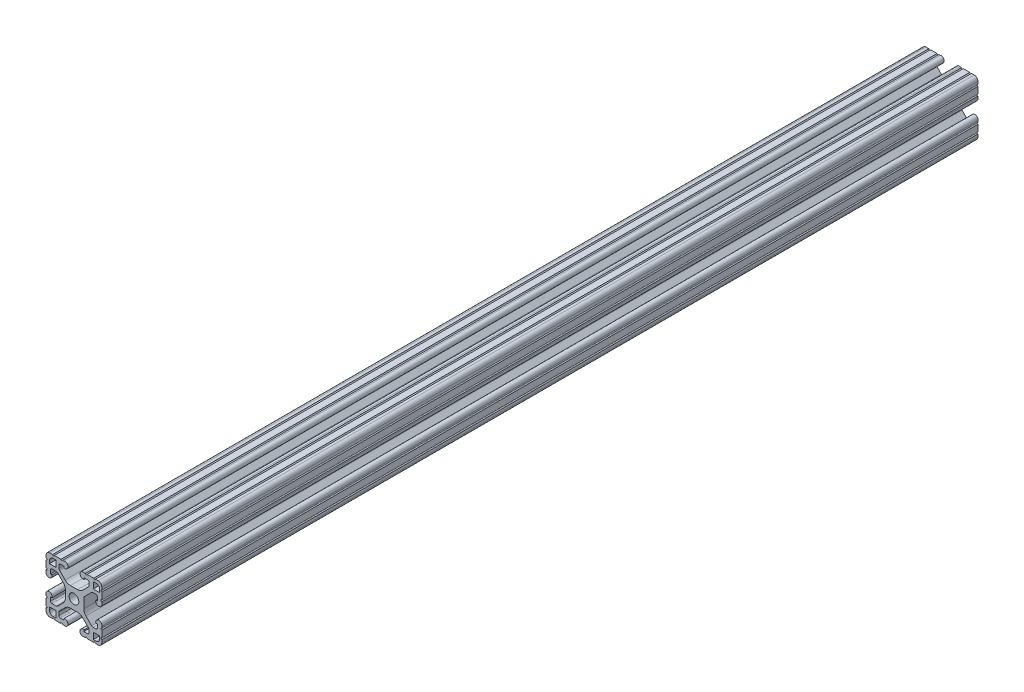
SolidWorks part; units mm, degrees
ref_plane "Front Plane" through (0, 0, 0) normal (0, 0, 1) x (1, 0, 0)
ref_plane "Top Plane" through (0, 0, 0) normal (0, 1, 0) x (1, 0, 0)
ref_plane "Right Plane" through (0, 0, 0) normal (1, 0, 0) x (0, 0, -1)
sketch "Sketch1" plane through (0, 0, 0) normal (0, 0, 1) x (1, 0, 0)
  line L56 (-13.2628, 12.0484) -> (-9.4662, 8.222)
  line L57 (-10.7901, 6.0082) -> (-14.6296, 9.8477)
  line L64 (6.4367, 12.0477) -> (2.5972, 8.2082)
  line L65 (3.2754, 4.5437) -> (8.5794, 9.8477)
  line L70 (-13.3201, -12.0484) -> (-9.5235, -8.222)
  line L71 (-14.6296, -9.8477) -> (-10.7901, -6.0082)
  line L76 (4.7399, -6.0082) -> (8.5794, -9.8477)
  line L77 (2.5399, -8.2082) -> (6.3794, -12.0477)
  line L102 (-5.9169, 6.7437) -> (-0.9384, 6.7437)
  line L103 (3.2754, 4.5437) -> (3.2754, -2.4726)
  line L104 (-0.9957, -6.7437) -> (-5.9742, -6.7437)
  line L105 (-9.3256, -2.4726) -> (-9.3256, 2.4726)
  line L141 (-7.5693, -19.05) -> (-7.5693, -14.986)
  line L153 (-18.4543, 6.801) -> (-19.4703, 6.801)
  line L156 (-19.4703, 6.801) -> (-19.4703, 9.287)
  line L158 (-10.212, 14.986) -> (-10.212, 15.986)
  line L159 (-10.212, 15.986) -> (-12.698, 15.986)
  line L163 (5.876, 15.986) -> (3.39, 15.986)
  line L164 (3.39, 14.986) -> (3.39, 15.986)
  line L167 (11.5177, 6.801) -> (12.5177, 6.801)
  line L168 (12.5177, 9.287) -> (12.5177, 6.801)
  line L171 (11.5177, -6.801) -> (12.5177, -6.801)
  line L172 (12.5177, -9.287) -> (12.5177, -6.801)
  line L174 (3.3327, -14.986) -> (3.3327, -15.986)
  line L175 (3.3327, -15.986) -> (5.8187, -15.986)
  line L179 (-12.7553, -15.986) -> (-10.2693, -15.986)
  line L180 (-10.2693, -14.986) -> (-10.2693, -15.986)
  line L181 (-18.4543, -6.801) -> (-19.4543, -6.801)
  line L184 (-19.4543, -6.801) -> (-19.4543, -9.287)
  line L185 (-18.4543, -10.287) -> (-15.6902, -10.287)
  line L186 (-13.7553, -14.986) -> (-13.7553, -13.1049)
  line L187 (6.8187, -14.986) -> (6.8187, -13.1083)
  line L188 (9.64, -10.287) -> (11.5177, -10.287)
  line L189 (9.64, 10.287) -> (11.5177, 10.287)
  line L190 (6.876, 13.1083) -> (6.876, 14.986)
  line L191 (-15.6902, 10.287) -> (-18.4703, 10.287)
  line L192 (-13.698, 13.1049) -> (-13.698, 14.986)
  line L193 (14.1589, 12.5213) -> (14.1589, 14.4213)
  line L198 (14.1589, 12.5213) -> (9.7589, 12.5213)
  line L199 (9.7589, 12.5213) -> (9.7589, 16.9213)
  line L200 (-15.8411, 12.5213) -> (-20.2411, 12.5213)
  line L201 (-15.8411, 12.5213) -> (-15.8411, 16.9213)
  line L202 (-15.8411, 16.9213) -> (-17.7411, 16.9213)
  line L203 (-20.2411, 12.5213) -> (-20.2411, 14.4213)
  line L204 (11.6589, 16.9213) -> (9.7589, 16.9213)
  line L205 (-15.8411, -17.4787) -> (-15.8411, -13.0787)
  line L206 (-15.8411, -17.4787) -> (-17.7411, -17.4787)
  line L207 (-20.2411, -14.9787) -> (-20.2411, -13.0787)
  line L208 (-15.8411, -13.0787) -> (-20.2411, -13.0787)
  line L209 (14.1589, -14.9787) -> (14.1589, -13.0787)
  line L210 (14.1589, -13.0787) -> (9.7589, -13.0787)
  line L211 (9.7589, -17.4787) -> (9.7589, -13.0787)
  line L212 (11.6589, -17.4787) -> (9.7589, -17.4787)
  line L213 (-20.0183, 19.05) -> (-18.0581, 19.05)
  line L214 (-16.8868, 19.05) -> (-12.3384, 19.05)
  line L215 (-11.1697, 19.05) -> (-10.212, 19.05)
  line L216 (-20.0183, -19.05) -> (-18.1417, -19.05)
  line L217 (-16.9879, -19.05) -> (-12.5275, -19.05)
  line L218 (-11.315, -19.05) -> (-10.2693, -19.05)
  line L219 (3.3327, -19.05) -> (4.3327, -19.05)
  line L220 (5.5555, -19.05) -> (10.0555, -19.05)
  line L221 (11.242, -19.05) -> (13.0817, -19.05)
  line L222 (3.39, 19.05) -> (4.39, 19.05)
  line L223 (5.5555, 19.05) -> (10.0555, 19.05)
  line L224 (11.242, 19.05) -> (13.0817, 19.05)
  line L225 (15.5817, 6.801) -> (15.5817, 7.791)
  line L226 (15.5817, 9.0004) -> (15.5817, 13.5141)
  line L227 (15.5817, -7.7849) -> (15.5817, -6.801)
  line L228 (15.5817, -8.9944) -> (15.5817, -13.5302)
  line L229 (15.5817, -16.55) -> (15.5817, -14.77)
  line L230 (15.5817, 16.55) -> (15.5817, 14.7019)
  line L231 (-22.5183, 6.801) -> (-22.5183, 7.791)
  line L232 (-22.5183, 9.0004) -> (-22.5183, 13.5141)
  line L233 (-22.5183, 14.7019) -> (-22.5183, 16.55)
  line L234 (-22.5183, -6.801) -> (-22.5183, -7.7849)
  line L235 (-22.5183, -8.9944) -> (-22.5183, -13.5302)
  line L236 (-22.5183, -16.55) -> (-22.5183, -14.77)
  circle A0 centre (-3.4683, 0) radius 3.3274
  arc A1 (-9.3256, 2.4726) -> (-10.7901, 6.0082) centre (-14.3256, 2.4726) ccw
  arc A2 (-9.3256, -2.4726) -> (-10.7901, -6.0082) centre (-14.3256, -2.4726) cw
  arc A3 (-5.9742, -6.7437) -> (-9.5235, -8.222) centre (-5.9742, -11.7437) ccw
  arc A4 (-0.9957, -6.7437) -> (2.5399, -8.2082) centre (-0.9957, -11.7437) cw
  arc A5 (3.2754, -2.4726) -> (4.7399, -6.0082) centre (8.2754, -2.4726) ccw
  arc A6 (-0.9384, 6.7437) -> (2.5972, 8.2082) centre (-0.9384, 11.7437) ccw
  arc A7 (-5.9169, 6.7437) -> (-9.4662, 8.222) centre (-5.9169, 11.7437) cw
  arc A8 (-15.6902, -10.287) -> (-14.6296, -9.8477) centre (-15.6902, -8.787) ccw
  arc A9 (-13.7553, -13.1049) -> (-13.3201, -12.0484) centre (-12.2553, -13.1049) cw
  arc A10 (6.8187, -13.1083) -> (6.3794, -12.0477) centre (5.3187, -13.1083) ccw
  arc A11 (9.64, -10.287) -> (8.5794, -9.8477) centre (9.64, -8.787) cw
  arc A12 (9.64, 10.287) -> (8.5794, 9.8477) centre (9.64, 8.787) ccw
  arc A13 (6.876, 13.1083) -> (6.4367, 12.0477) centre (5.376, 13.1083) cw
  arc A14 (-13.698, 13.1049) -> (-13.2628, 12.0484) centre (-12.198, 13.1049) ccw
  arc A15 (-15.6902, 10.287) -> (-14.6296, 9.8477) centre (-15.6902, 8.787) cw
  arc A16 (-22.5183, 6.801) -> (-18.4543, 6.801) centre (-20.4863, 6.2156) ccw
  arc A17 (-10.212, 14.986) -> (-10.212, 19.05) centre (-9.6266, 17.018) ccw
  arc A18 (3.39, 19.05) -> (3.39, 14.986) centre (2.8047, 17.018) ccw
  arc A19 (11.5177, 6.801) -> (15.5817, 6.801) centre (13.5497, 6.2156) ccw
  arc A20 (11.5177, -6.801) -> (15.5817, -6.801) centre (13.5497, -6.2156) cw
  arc A21 (3.3327, -14.986) -> (3.3327, -19.05) centre (2.7474, -17.018) ccw
  arc A22 (-10.2693, -19.05) -> (-10.2693, -14.986) centre (-9.6839, -17.018) ccw
  arc A23 (-22.5183, -6.801) -> (-18.4543, -6.801) centre (-20.4863, -6.2156) cw
  arc A24 (5.8187, -15.986) -> (6.8187, -14.986) centre (5.8187, -14.986) ccw
  arc A25 (-13.7553, -14.986) -> (-12.7553, -15.986) centre (-12.7553, -14.986) ccw
  arc A26 (-18.4543, -10.287) -> (-19.4543, -9.287) centre (-18.4543, -9.287) cw
  arc A27 (11.5177, -10.287) -> (12.5177, -9.287) centre (11.5177, -9.287) ccw
  arc A28 (11.5177, 10.287) -> (12.5177, 9.287) centre (11.5177, 9.287) cw
  arc A29 (6.876, 14.986) -> (5.876, 15.986) centre (5.876, 14.986) ccw
  arc A30 (-12.698, 15.986) -> (-13.698, 14.986) centre (-12.698, 14.986) ccw
  arc A31 (-18.4703, 10.287) -> (-19.4703, 9.287) centre (-18.4703, 9.287) ccw
  arc A32 (-20.0183, -19.05) -> (-22.5183, -16.55) centre (-20.0183, -16.55) cw
  arc A33 (13.0817, -19.05) -> (15.5817, -16.55) centre (13.0817, -16.55) ccw
  arc A34 (15.5817, 16.55) -> (13.0817, 19.05) centre (13.0817, 16.55) ccw
  arc A35 (-20.0183, 19.05) -> (-22.5183, 16.55) centre (-20.0183, 16.55) ccw
  arc A36 (14.1589, -14.9787) -> (11.6589, -17.4787) centre (11.6589, -14.9787) cw
  arc A37 (-17.7411, -17.4787) -> (-20.2411, -14.9787) centre (-17.7411, -14.9787) cw
  arc A38 (14.1589, 14.4213) -> (11.6589, 16.9213) centre (11.6589, 14.4213) ccw
  arc A39 (-17.7411, 16.9213) -> (-20.2411, 14.4213) centre (-17.7411, 14.4213) ccw
  arc A40 (-11.315, -19.05) -> (-12.5275, -19.05) centre (-11.9213, -19.05) ccw
  arc A41 (-18.1417, -19.05) -> (-16.9879, -19.05) centre (-17.5648, -19.05) cw
  arc A42 (4.3327, -19.05) -> (5.5555, -19.05) centre (4.9441, -19.05) cw
  arc A43 (10.0555, -19.05) -> (11.242, -19.05) centre (10.6488, -19.05) cw
  arc A44 (-11.1697, 19.05) -> (-12.3384, 19.05) centre (-11.754, 19.05) cw
  arc A45 (-16.8868, 19.05) -> (-18.0581, 19.05) centre (-17.4724, 19.05) cw
  arc A46 (4.39, 19.05) -> (5.5555, 19.05) centre (4.9727, 19.05) ccw
  arc A47 (10.0555, 19.05) -> (11.242, 19.05) centre (10.6488, 19.05) ccw
  arc A48 (15.5817, 7.791) -> (15.5817, 9.0004) centre (15.5817, 8.3957) cw
  arc A49 (15.5817, 13.5141) -> (15.5817, 14.7019) centre (15.5817, 14.108) cw
  arc A50 (15.5817, -7.7849) -> (15.5817, -8.9944) centre (15.5817, -8.3897) ccw
  arc A51 (15.5817, -13.5302) -> (15.5817, -14.77) centre (15.5817, -14.1501) ccw
  arc A52 (-22.5183, 7.791) -> (-22.5183, 9.0004) centre (-22.5183, 8.3957) ccw
  arc A53 (-22.5183, 13.5141) -> (-22.5183, 14.7019) centre (-22.5183, 14.108) ccw
  arc A54 (-22.5183, -7.7849) -> (-22.5183, -8.9944) centre (-22.5183, -8.3897) cw
  arc A55 (-22.5183, -13.5302) -> (-22.5183, -14.77) centre (-22.5183, -14.1501) cw
  point P0 (0, 0)
  point P6 (0, 0)
  point P123 (-22.5183, -19.05)
  point P128 (15.5817, 19.05)
  point P131 (-22.5183, 19.05)
  point P157 (-20.2411, 16.9213)
  dimension "D33" = 6.6548
  dimension "D9" = 5
  dimension "D10" = 1.5
  dimension "D4" = 1
  dimension "D8" = 2.5
  dimension "D21" = 2.5
  dimension "D1" = 38.1
  dimension "D2" = 38.1
  dimension "D5" = 2.7
  dimension "D6" = 1.016
  dimension "D7" = 1
  dimension "D11" = 2
  dimension "D12" = 1
  dimension "D13" = 1
  dimension "D14" = 2
  dimension "D15" = 1
  dimension "D16" = 4.064
  dimension "D17" = 1
  dimension "D18" = 4.4
  dimension "D19" = 4.4
  dimension "D20" = 2
  dimension "D22" = 1.0457
  dimension "D23" = 1
  dimension "D24" = 4.4604
  dimension "D25" = 4.5
  dimension "D26" = 1
extrude "Boss-Extrude1" add sketch "Sketch1" along normal blind 600
